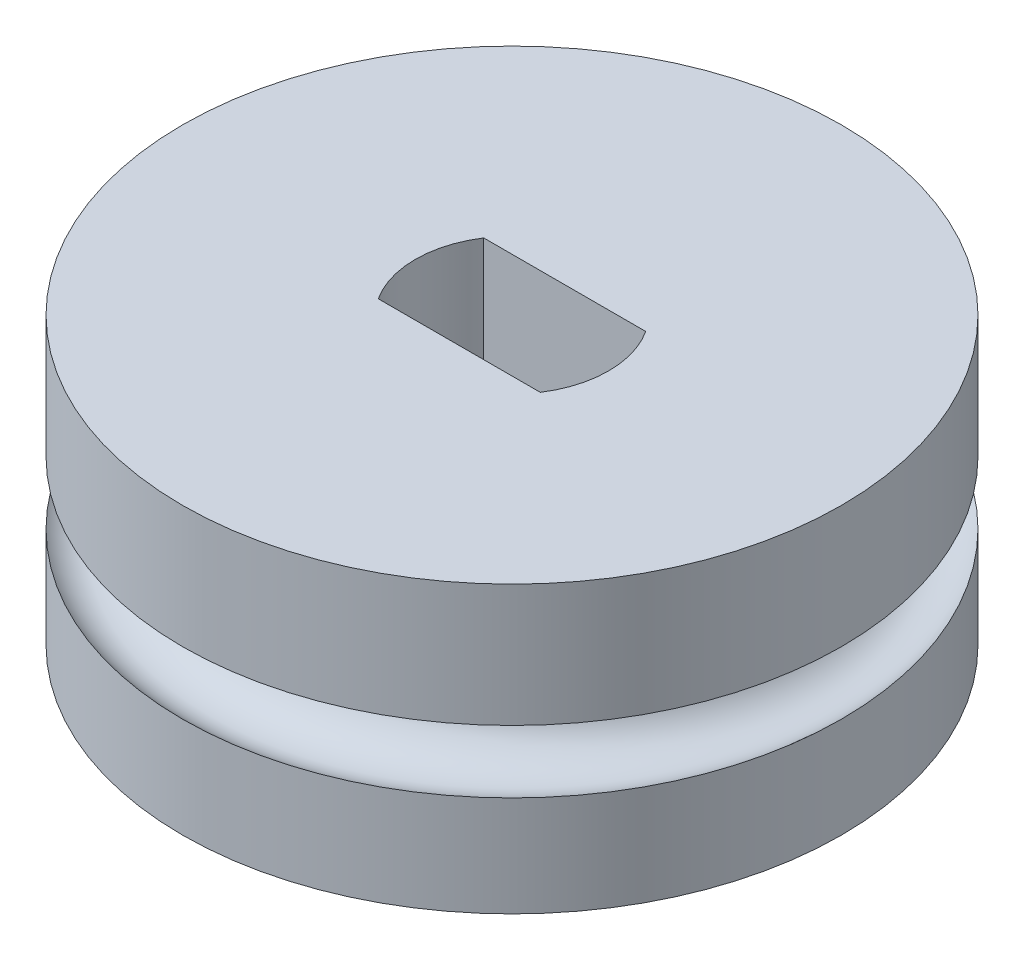
SolidWorks part; units mm, degrees
ref_plane "前视基准面" through (0, 0, 0) normal (0, 0, 1) x (1, 0, 0)
ref_plane "上视基准面" through (0, 0, 0) normal (0, 1, 0) x (1, 0, 0)
ref_plane "右视基准面" through (0, 0, 0) normal (1, 0, 0) x (0, 0, -1)
other "Configuration Table"
sketch "草图1" plane through (0, 0, 0) normal (0, 1, 0) x (1, 0, 0)
  circle A0 centre (0, 0) radius 2.75
  dimension "D1" = 5.5
extrude "凸台-拉伸1" add sketch "草图1" along normal blind 8
sketch "草图2" plane through (0, 8, 0) normal (0, 1, 0) x (1, 0, 0)
  line L0 (-1.8439, 1.2) -> (1.8439, 1.2)
  line L1 (-1.8439, -1.2) -> (1.8439, -1.2)
  circle A0 centre (0, 0) radius 2.2
  dimension "D1" = 4.4
  dimension "D2" = 2.4
extrude "切除-拉伸1" cut sketch "草图2" against normal offset from surface (7 mm away) 1 contours L1 A0 L0 up to face at (0, 0, 2.75)
sketch "草图4" plane through (0, 8, 0) normal (0, 1, 0) x (1, 0, 0)
  line L2 (1.6363, -1.15) -> (-1.6363, -1.15)
  line L3 (1.6363, 1.15) -> (-1.6363, 1.15)
  circle A0 centre (0, 0) radius 2
  circle A1 centre (0, 0) radius 2 construction
  circle A2 centre (0, 0) radius 2
  line M1 (1.8439, -1.2) -> (-1.8439, -1.2)
  line M3 (-1.8439, 1.2) -> (1.8439, 1.2)
  dimension "D1" = 4
  dimension "D2" = 2.3
extrude "凸台-拉伸2" add sketch "草图4" along normal blind 3.5 contours A0 M3 | A0 M1
sketch "草图5" plane through (0, 8, 0) normal (0, 1, 0) x (1, 0, 0)
  circle A0 centre (0, 0) radius 7.5
  circle A1 centre (0, 0) radius 2.75
  circle A2 centre (0, 0) radius 2.75
  dimension "D2" = 15
  dimension "D1" = 0
extrude "凸台-拉伸3" add sketch "草图5" against normal up to surface (8 mm away) up to face at (0, 0, 2.75)
ref_plane "基准面1" through (0, 4, 0) normal (0, -1, 0) x (-1, 0, 0)
ref_plane "基准面2" through (0, 4.5, 0) normal (0, -1, 0) x (-1, 0, 0)
ref_plane "基准面3" through (0, 6, 0) normal (0, 1, 0) x (1, 0, 0)
sketch "草图16" plane through (0, 4.5, 0) normal (0, -1, 0) x (-1, 0, 0)
  circle A0 centre (0, 0) radius 6.8
  circle A1 centre (0, 0) radius 7.5 construction
  dimension "D1" = 0.7
sweep "切除-扫描1" cut path "草图16" circular profile diameter 2 parameters "D3"=2
sketch "草图47" plane through (0, 0, 0) normal (0, -1, 0) x (1, 0, 0)
  circle A0 centre (0, 0) radius 3.25
  circle A1 centre (0, 0) radius 7.5 construction
  circle A3 centre (0, 0) radius 7.5
  circle M2 centre (0, 0) radius 7.5
  dimension "D1" = 6.5
extrude "切除-拉伸3" cut sketch "草图47" against normal blind 1.5 contours A0 M2
sketch "草图48" plane through (0, 1.5, 0) normal (0, -1, 0) x (1, 0, 0)
  circle A0 centre (-5.7, 0) radius 0.8
  circle A1 centre (0, 0) radius 7.5 construction
  dimension "D1" = 1.6
  dimension "D2" = 5.7
extrude "切除-拉伸4" cut sketch "草图48" against normal blind 3.7
sketch "草图56" plane through (0, 8, 0) normal (0, 1, 0) x (1, 0, 0)
  line L0 (1.6, -1.2) -> (-1.6, -1.2) construction
  line L1 (-1.6, 1.2) -> (1.6, 1.2) construction
  line L2 (1.6, -1.2) -> (-1.6, -1.2)
  line L3 (-1.6, 1.2) -> (1.6, 1.2)
  arc A0 (-1.6, -1.2) -> (1.6, -1.2) centre (0, 0) ccw construction
  arc A1 (1.6, 1.2) -> (-1.6, 1.2) centre (0, 0) ccw construction
  arc A2 (-1.6, -1.2) -> (1.6, -1.2) centre (0, 0) ccw
  arc A3 (1.6, 1.2) -> (-1.6, 1.2) centre (0, 0) ccw
extrude "切除-拉伸6" cut sketch "草图56" along normal up to surface (3.5 mm away) up to face at (0, 11.5, 1.6)
